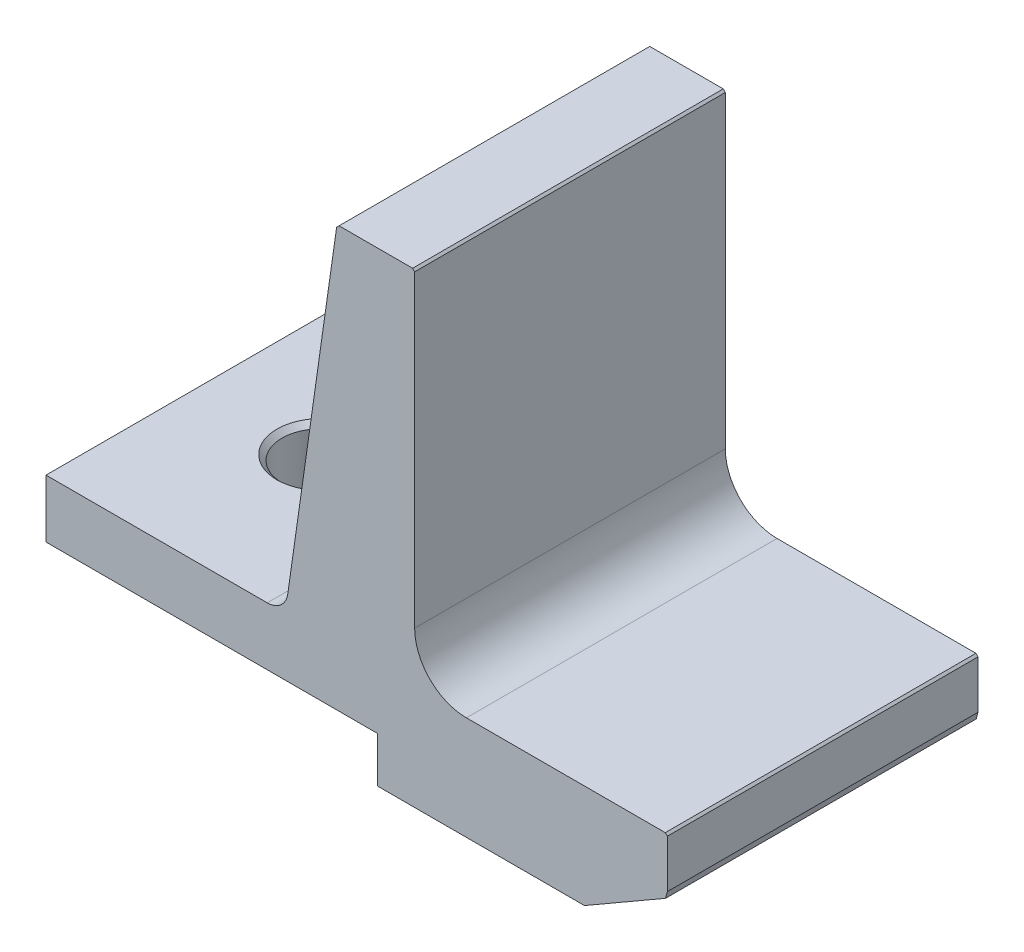
SolidWorks part; units mm, degrees
ref_plane "Front Plane" through (0, 0, 0) normal (0, 0, 1) x (1, 0, 0)
ref_plane "Top Plane" through (0, 0, 0) normal (0, 1, 0) x (1, 0, 0)
ref_plane "Right Plane" through (0, 0, 0) normal (1, 0, 0) x (0, 0, -1)
sketch "Sketch1" plane through (0, 0, 0) normal (0, 0, 1) x (1, 0, 0)
  line L0 (0, 0) -> (30.988, 0)
  line L1 (30.988, 0) -> (30.988, -12.7)
  line L2 (30.988, -12.7) -> (-4.572, -12.7)
  line L3 (-45.212, -7.112) -> (-45.212, 0)
  line L4 (-45.212, 0) -> (-15.875, 0)
  line L5 (-15.875, 0) -> (-9.525, 44.45)
  line L6 (-9.525, 44.45) -> (0, 44.45)
  line L7 (0, 44.45) -> (0, 0)
  line L8 (-4.572, -12.7) -> (-4.572, -7.112)
  line L9 (-4.572, -7.112) -> (-45.212, -7.112)
  dimension "D1" = 30.988
  dimension "D2" = 44.45
  dimension "D3" = 12.7
  dimension "D4" = 76.2
  dimension "D5" = 9.525
  dimension "D6" = 5.588
  dimension "D7" = 40.64
  dimension "D8" = 15.875
extrude "Boss-Extrude1" add sketch "Sketch1" along normal blind 38.1
hole_wizard "3/8 (0.375) Diameter Hole1" positions "Sketch5" profile "Sketch3" hole size "3/8" standard "ANSI Inch" end condition through all
sketch "Sketch5" plane through (0, 0, 0) normal (0, 1, 0) x (1, 0, 0)
  line L0 (-15.875, 0) -> (-45.212, 0) construction
  point P0 (-30.5435, -19.05)
  point P5 (-30.5435, 0)
sketch "Sketch3" plane through (-30.5435, 0, 19.05) normal (1, 0, 0) x (0, 0, 1)
  line L0 (0, 0) -> (0, 12.7)
  line L1 (0, 12.7) -> (4.7625, 12.7)
  line L2 (4.7625, 12.7) -> (4.7625, 0.635)
  line L3 (4.7625, 0.635) -> (5.3975, 0)
  line L5 (5.3975, 0) -> (0, 0)
  line L6 (-4.7625, 0.635) -> (-5.3975, 0) construction
  line L11 (0, -6.35) -> (0, 107.95) construction
  dimension "Thru Hole Dia." = 9.525
  dimension "Thru Hole Depth" = 12.7
  dimension "Near C'Sink Dia." = 10.795
  dimension "Near C'Sink Angle" = 90
chamfer "Chamfer1" distance 10.16 angle 30 1 edges at (30.988, -12.7, 19.05)
fillet "Fillet1" radius 2.54 1 edges at (-15.875, 0, 19.05)
fillet "Fillet2" radius 6.35 1 edges at (0, 0, 19.05)
chamfer "Chamfer2" distance 0.254 angle 45 4 edges at (30.988, -6.8341, 19.05) (30.988, 0, 19.05) (0, 44.45, 19.05) (-9.525, 44.45, 19.05)
